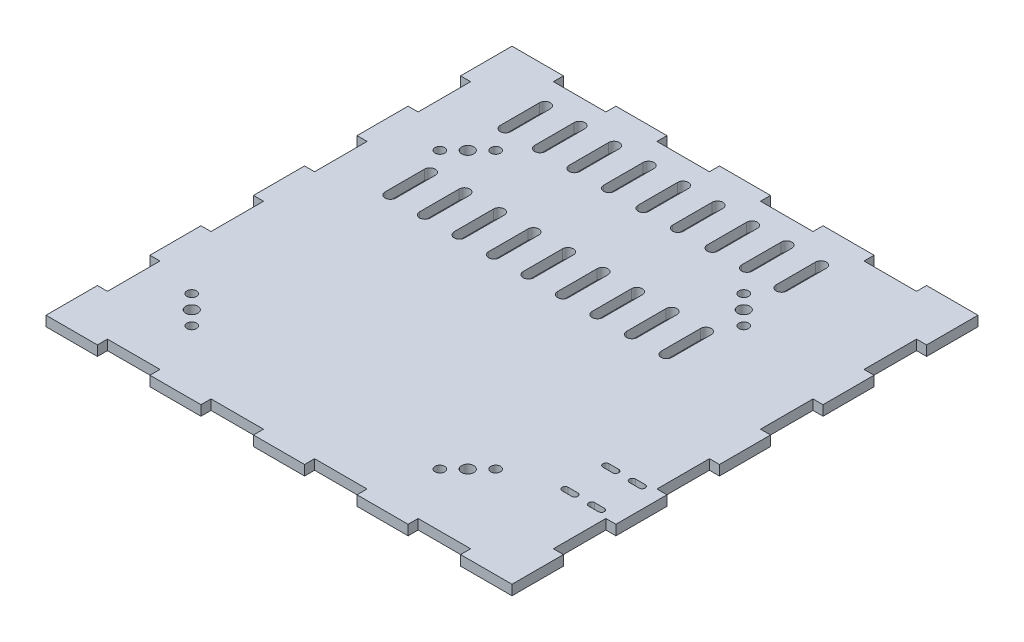
SolidWorks part; units mm, degrees
material "Acrylic (Medium-high impact)"
ref_plane "Front Plane" through (0, 0, 0) normal (0, 0, 1) x (1, 0, 0)
ref_plane "Top Plane" through (0, 0, 0) normal (0, 1, 0) x (1, 0, 0)
ref_plane "Right Plane" through (0, 0, 0) normal (1, 0, 0) x (0, 0, -1)
sketch "Board refrence" plane through (0, 0, 0) normal (0, 1, 0) x (1, 0, 0)
  line L0 (45, -19.76) -> (50, -19.76)
  line L1 (-42.5, -42.5) -> (42.5, -42.5)
  line L2 (-42.5, -42.5) -> (-42.5, 42.5)
  line L3 (-42.5, 42.5) -> (42.5, 42.5)
  line L4 (42.5, -42.5) -> (42.5, 42.5)
  line L5 (-42.5, -42.5) -> (42.5, 42.5) construction
  line L6 (-42.5, 42.5) -> (42.5, -42.5) construction
  line L7 (-50.8, 48.85) -> (50.8, 48.85)
  line L8 (-50.8, 48.85) -> (-50.8, 42.5)
  line L9 (-50.8, 42.5) -> (50.8, 42.5)
  line L10 (50.8, 48.85) -> (50.8, 42.5)
  line L11 (45, -27.76) -> (50, -27.76)
  line L12 (47.5, -27.76) -> (47.5, -19.76) construction
  circle A0 centre (-38.5, 38.5) radius 1.6
  circle A1 centre (-38.5, -38.5) radius 1.6
  circle A2 centre (38.5, -38.5) radius 1.6
  circle A3 centre (38.5, 38.5) radius 1.6
  point P0 (0, 0)
  point P14 (0, 42.5)
  point P15 (0, 42.5)
  point P26 (47.5, -23.76)
  dimension "D4" = 3.2
  dimension "D1" = 85
  dimension "D2" = 85
  dimension "D3" = 4
  dimension "D5" = 6.35
  dimension "D6" = 101.6
  dimension "D7" = 18.74
  dimension "D8" = 8
  dimension "D9" = 5
  dimension "D10" = 5
sketch "Sketch2" plane through (0, 0, 0) normal (0, 1, 0) x (1, 0, 0)
  line L0 (-42.5, -42.5) -> (-42.5, 42.5) construction
  line L1 (-54.3, 66.65) -> (69.3, 66.65) construction
  line L2 (-54.3, 66.65) -> (-54.3, -56.95) construction
  line L3 (-54.3, -56.95) -> (69.3, -56.95) construction
  line L4 (69.3, 66.65) -> (69.3, -56.95) construction
  line L6 (42.5, -42.5) -> (42.5, 42.5) construction
  line L7 (-50.8, 48.85) -> (50.8, 48.85) construction
  line L8 (-57.5, 69.85) -> (-57.5, -60.15)
  line L9 (-57.5, -60.15) -> (72.5, -60.15)
  line L10 (72.5, 69.85) -> (72.5, -60.15)
  line L11 (-57.5, 69.85) -> (72.5, 69.85)
  circle A0 centre (-38.5, 38.5) radius 1.7
  circle A1 centre (-38.5, -38.5) radius 1.7
  circle A2 centre (38.5, -38.5) radius 1.7
  circle A3 centre (38.5, 38.5) radius 1.7
  point P16 (0, 0)
  dimension "D1" = 3.4
  dimension "D2" = 15
  dimension "D3" = 21
  dimension "D4" = 30
  dimension "D6" = 130
  dimension "D5" = 3.2
extrude "Boss-Extrude1" add sketch "Sketch2" along normal blind 2.8
sketch "Sketch5" plane through (0, 2.8, 0) normal (0, 1, 0) x (1, 0, 0)
  line L0 (34.6109, 42.3891) -> (42.3891, 34.6109) construction
  line L1 (72.5, -60.15) -> (72.5, 69.85) construction
  circle A0 centre (42.3891, 34.6109) radius 1.35
  circle A1 centre (34.6109, 42.3891) radius 1.35
  circle A2 centre (34.6109, -42.3891) radius 1.35
  circle A3 centre (42.3891, -34.6109) radius 1.35
  circle A4 centre (-42.3891, -34.6109) radius 1.35
  circle A5 centre (-34.6109, -42.3891) radius 1.35
  circle A6 centre (-34.6109, 42.3891) radius 1.35
  circle A7 centre (-42.3891, 34.6109) radius 1.35
  point P4 (38.5, 38.5)
  point P23 (0, 0)
  dimension "D3" = 2.7
  dimension "D1" = 45
  dimension "D2" = 11
extrude "Cut-Extrude2" cut sketch "Sketch5" against normal up to next
sketch "Sketch4" plane through (0, 2.8, 0) normal (0, 1, 0) x (1, 0, 0)
  line L0 (72.5, 55.4056) -> (72.5, 40.9611)
  line L1 (72.5, -60.15) -> (72.5, 69.85) construction
  line L2 (72.5, 12.0722) -> (69.7, 12.0722)
  line L3 (69.7, 12.0722) -> (69.7, 26.5167)
  line L4 (69.7, 26.5167) -> (72.5, 26.5167)
  line L5 (72.5, 26.5167) -> (72.5, 12.0722)
  line L6 (72.5, -16.8167) -> (69.7, -16.8167)
  line L7 (69.7, -16.8167) -> (69.7, -2.3722)
  line L8 (69.7, -2.3722) -> (72.5, -2.3722)
  line L9 (72.5, -2.3722) -> (72.5, -16.8167)
  line L10 (72.5, 40.9611) -> (69.7, 40.9611)
  line L11 (69.7, 40.9611) -> (69.7, 55.4056)
  line L12 (69.7, 55.4056) -> (72.5, 55.4056)
  line L13 (72.5, -45.7056) -> (69.7, -45.7056)
  line L14 (69.7, -45.7056) -> (69.7, -31.2611)
  line L15 (69.7, -31.2611) -> (72.5, -31.2611)
  line L16 (72.5, -31.2611) -> (72.5, -45.7056)
  line L17 (72.5, 40.9611) -> (72.5, 12.0722) construction
  line L18 (69.7, -45.7056) -> (69.7, -60.15) construction
  line L19 (-57.5, -60.15) -> (72.5, -60.15) construction
  line L20 (69.7, -31.2611) -> (69.7, -16.8167) construction
  line L21 (72.5, 69.85) -> (-57.5, 69.85) construction
  line L42 (-57.5, 69.85) -> (72.5, -60.15) construction
  line L66 (-43.0556, -60.15) -> (-43.0556, -57.35)
  line L67 (-43.0556, -57.35) -> (-28.6111, -57.35)
  line L68 (-28.6111, -57.35) -> (-28.6111, -60.15)
  line L91 (69.7, -2.3722) -> (69.7, 12.0722) construction
  line L92 (69.7, 26.5167) -> (69.7, 40.9611) construction
  line L93 (69.7, 55.4056) -> (69.7, 69.85) construction
  line L94 (-28.6111, -60.15) -> (-43.0556, -60.15)
  line L95 (-14.1667, -60.15) -> (-14.1667, -57.35)
  line L96 (-14.1667, -57.35) -> (0.2778, -57.35)
  line L97 (0.2778, -57.35) -> (0.2778, -60.15)
  line L103 (0.2778, -60.15) -> (-14.1667, -60.15)
  line L108 (14.7222, -60.15) -> (14.7222, -57.35)
  line L113 (14.7222, -57.35) -> (29.1667, -57.35)
  line L118 (29.1667, -57.35) -> (29.1667, -60.15)
  line L119 (29.1667, -60.15) -> (14.7222, -60.15)
  line L120 (58.0556, -60.15) -> (43.6111, -60.15)
  line L121 (43.6111, -60.15) -> (43.6111, -57.35)
  line L125 (43.6111, -57.35) -> (58.0556, -57.35)
  line L126 (58.0556, -57.35) -> (58.0556, -60.15)
  line L127 (-57.5, 55.4056) -> (-54.7, 55.4056)
  line L128 (-54.7, 55.4056) -> (-54.7, 40.9611)
  line L129 (-54.7, 40.9611) -> (-57.5, 40.9611)
  line L130 (-57.5, 40.9611) -> (-57.5, 55.4056)
  line L131 (-57.5, 26.5167) -> (-54.7, 26.5167)
  line L132 (-54.7, 26.5167) -> (-54.7, 12.0722)
  line L133 (-54.7, 12.0722) -> (-57.5, 12.0722)
  line L134 (-57.5, 12.0722) -> (-57.5, 26.5167)
  line L135 (-57.5, -2.3722) -> (-54.7, -2.3722)
  line L136 (-54.7, -2.3722) -> (-54.7, -16.8167)
  line L137 (-54.7, -16.8167) -> (-57.5, -16.8167)
  line L138 (-57.5, -16.8167) -> (-57.5, -2.3722)
  line L139 (-57.5, -45.7056) -> (-57.5, -31.2611)
  line L140 (-57.5, -31.2611) -> (-54.7, -31.2611)
  line L141 (-54.7, -31.2611) -> (-54.7, -45.7056)
  line L142 (-54.7, -45.7056) -> (-57.5, -45.7056)
  line L143 (58.0556, 69.85) -> (58.0556, 67.05)
  line L144 (58.0556, 67.05) -> (43.6111, 67.05)
  line L145 (43.6111, 67.05) -> (43.6111, 69.85)
  line L146 (43.6111, 69.85) -> (58.0556, 69.85)
  line L147 (29.1667, 69.85) -> (29.1667, 67.05)
  line L148 (29.1667, 67.05) -> (14.7222, 67.05)
  line L149 (14.7222, 67.05) -> (14.7222, 69.85)
  line L150 (14.7222, 69.85) -> (29.1667, 69.85)
  line L151 (0.2778, 69.85) -> (0.2778, 67.05)
  line L152 (0.2778, 67.05) -> (-14.1667, 67.05)
  line L153 (-14.1667, 67.05) -> (-14.1667, 69.85)
  line L154 (-14.1667, 69.85) -> (0.2778, 69.85)
  line L155 (-43.0556, 69.85) -> (-28.6111, 69.85)
  line L156 (-28.6111, 69.85) -> (-28.6111, 67.05)
  line L157 (-28.6111, 67.05) -> (-43.0556, 67.05)
  line L158 (-43.0556, 67.05) -> (-43.0556, 69.85)
  point P27 (7.5, 4.85)
  point P81 (7.5, 4.85)
  dimension "D4" = 2.8
  dimension "D1" = 4
  dimension "D2" = 4
extrude "Cut-Extrude1" cut sketch "Sketch4" against normal through all
sketch "Pad reference" plane through (0, 2.8, 0) normal (0, 1, 0) x (1, 0, 0)
  line L151 (72.5, -60.15) -> (72.5, -45.7056) construction
  line L152 (72.5, 69.85) -> (58.0556, 69.85) construction
  line L153 (-50.5, -53.15) -> (-43.0556, -53.15)
  line L154 (-50.5, -45.7056) -> (-50.5, -53.15)
  line L155 (-50.5, -53.15) -> (-43.0556, -53.15) construction
  line L156 (-50.5, -45.7056) -> (-50.5, -53.15) construction
  circle A0 centre (-50.5, 62.85) radius 4
  circle A1 centre (65.5, 62.85) radius 4
  circle A2 centre (65.5, -53.15) radius 4
  circle A3 centre (-50.5, -53.15) radius 4
  dimension "D1" = 8
  dimension "D3" = 7
  dimension "D4" = 7
  dimension "D2" = 7
sketch "Sketch6" plane through (0, 2.8, 0) normal (0, 1, 0) x (1, 0, 0)
  line L0 (67, -29.7389) -> (64.3, -29.7389) construction
  line L1 (67, -30.5889) -> (64.3, -30.5889)
  line L2 (67, -28.8889) -> (64.3, -28.8889)
  line L3 (59.6, -29.7389) -> (56.9, -29.7389) construction
  line L4 (59.6, -30.5889) -> (56.9, -30.5889)
  line L5 (59.6, -28.8889) -> (56.9, -28.8889)
  line L6 (72.5, -24.0389) -> (-49927.5, -24.0389) construction
  line L7 (72.5, -31.2611) -> (72.5, -16.8167) construction
  line L8 (59.6, -18.3389) -> (56.9, -18.3389) construction
  line L9 (59.6, -17.4889) -> (56.9, -17.4889)
  line L10 (59.6, -19.1889) -> (56.9, -19.1889)
  line L11 (67, -18.3389) -> (64.3, -18.3389) construction
  line L12 (67, -17.4889) -> (64.3, -17.4889)
  line L13 (67, -19.1889) -> (64.3, -19.1889)
  arc A0 (67, -30.5889) -> (67, -28.8889) centre (67, -29.7389) ccw
  arc A1 (64.3, -28.8889) -> (64.3, -30.5889) centre (64.3, -29.7389) ccw
  arc A2 (59.6, -30.5889) -> (59.6, -28.8889) centre (59.6, -29.7389) ccw
  arc A3 (56.9, -28.8889) -> (56.9, -30.5889) centre (56.9, -29.7389) ccw
  arc A4 (59.6, -17.4889) -> (59.6, -19.1889) centre (59.6, -18.3389) cw
  arc A5 (56.9, -19.1889) -> (56.9, -17.4889) centre (56.9, -18.3389) cw
  arc A6 (67, -17.4889) -> (67, -19.1889) centre (67, -18.3389) cw
  arc A7 (64.3, -19.1889) -> (64.3, -17.4889) centre (64.3, -18.3389) cw
  point P2 (65.65, -29.7389)
  point P7 (58.25, -29.7389)
  point P18 (72.5, -24.0389)
  point P21 (58.25, -18.3389)
  point P28 (65.65, -18.3389)
  dimension "D3" = 3
  dimension "D1" = 4.4
  dimension "D2" = 1.7
  dimension "D4" = 4.85
  dimension "D5" = 5.5
extrude "Cut-Extrude3" cut sketch "Sketch6" against normal up to next
sketch "Sketch7" plane through (0, 2.8, 0) normal (0, 1, 0) x (1, 0, 0)
  line L0 (-38.5, 60.05) -> (-38.5, 49.05) construction
  line L1 (-37, 60.05) -> (-37, 49.05)
  line L2 (-40, 60.05) -> (-40, 49.05)
  line L3 (-43.0556, 67.05) -> (-28.6111, 67.05) construction
  line L5 (-30.375, 60.05) -> (-30.375, 49.05)
  line L6 (-27.375, 60.05) -> (-27.375, 49.05)
  line L7 (-28.875, 60.05) -> (-28.875, 49.05) construction
  line L8 (-20.75, 60.05) -> (-20.75, 49.05)
  line L9 (-17.75, 60.05) -> (-17.75, 49.05)
  line L10 (-19.25, 60.05) -> (-19.25, 49.05) construction
  line L11 (-11.125, 60.05) -> (-11.125, 49.05)
  line L12 (-8.125, 60.05) -> (-8.125, 49.05)
  line L13 (-9.625, 60.05) -> (-9.625, 49.05) construction
  line L14 (-1.5, 60.05) -> (-1.5, 49.05)
  line L15 (1.5, 60.05) -> (1.5, 49.05)
  line L16 (0, 60.05) -> (0, 49.05) construction
  line L17 (8.125, 60.05) -> (8.125, 49.05)
  line L18 (11.125, 60.05) -> (11.125, 49.05)
  line L19 (9.625, 60.05) -> (9.625, 49.05) construction
  line L20 (17.75, 60.05) -> (17.75, 49.05)
  line L21 (20.75, 60.05) -> (20.75, 49.05)
  line L22 (19.25, 60.05) -> (19.25, 49.05) construction
  line L23 (27.375, 60.05) -> (27.375, 49.05)
  line L24 (30.375, 60.05) -> (30.375, 49.05)
  line L25 (28.875, 60.05) -> (28.875, 49.05) construction
  line L26 (37, 60.05) -> (37, 49.05)
  line L27 (40, 60.05) -> (40, 49.05)
  line L28 (38.5, 60.05) -> (38.5, 49.05) construction
  line L31 (-40, 27.95) -> (-40, 16.95)
  line L32 (-38.5, 38.5) -> (-38.5, 49.05) construction
  line L33 (-38.5, 38.5) -> (-38.5, 27.95) construction
  line L35 (-37, 27.95) -> (-37, 16.95)
  line L36 (-38.5, 27.95) -> (-38.5, 16.95) construction
  line L37 (-30.375, 27.95) -> (-30.375, 16.95)
  line L38 (-27.375, 27.95) -> (-27.375, 16.95)
  line L39 (-28.875, 27.95) -> (-28.875, 16.95) construction
  line L40 (-20.75, 27.95) -> (-20.75, 16.95)
  line L41 (-17.75, 27.95) -> (-17.75, 16.95)
  line L42 (-19.25, 27.95) -> (-19.25, 16.95) construction
  line L43 (-11.125, 27.95) -> (-11.125, 16.95)
  line L44 (-8.125, 27.95) -> (-8.125, 16.95)
  line L45 (-9.625, 27.95) -> (-9.625, 16.95) construction
  line L46 (-1.5, 27.95) -> (-1.5, 16.95)
  line L47 (1.5, 27.95) -> (1.5, 16.95)
  line L48 (0, 27.95) -> (0, 16.95) construction
  line L49 (8.125, 27.95) -> (8.125, 16.95)
  line L50 (11.125, 27.95) -> (11.125, 16.95)
  line L51 (9.625, 27.95) -> (9.625, 16.95) construction
  line L52 (17.75, 27.95) -> (17.75, 16.95)
  line L53 (20.75, 27.95) -> (20.75, 16.95)
  line L54 (19.25, 27.95) -> (19.25, 16.95) construction
  line L55 (27.375, 27.95) -> (27.375, 16.95)
  line L56 (30.375, 27.95) -> (30.375, 16.95)
  line L57 (28.875, 27.95) -> (28.875, 16.95) construction
  line L58 (37, 27.95) -> (37, 16.95)
  line L59 (40, 27.95) -> (40, 16.95)
  line L60 (38.5, 27.95) -> (38.5, 16.95) construction
  line L61 (38.5, 27.95) -> (38.5, 38.5) construction
  line L62 (38.5, 38.5) -> (38.5, 49.05) construction
  arc A0 (-37, 60.05) -> (-40, 60.05) centre (-38.5, 60.05) ccw
  arc A1 (-40, 49.05) -> (-37, 49.05) centre (-38.5, 49.05) ccw
  arc A2 (-27.375, 60.05) -> (-30.375, 60.05) centre (-28.875, 60.05) ccw
  arc A3 (-30.375, 49.05) -> (-27.375, 49.05) centre (-28.875, 49.05) ccw
  arc A4 (-17.75, 60.05) -> (-20.75, 60.05) centre (-19.25, 60.05) ccw
  arc A5 (-20.75, 49.05) -> (-17.75, 49.05) centre (-19.25, 49.05) ccw
  arc A6 (-8.125, 60.05) -> (-11.125, 60.05) centre (-9.625, 60.05) ccw
  arc A7 (-11.125, 49.05) -> (-8.125, 49.05) centre (-9.625, 49.05) ccw
  arc A8 (1.5, 60.05) -> (-1.5, 60.05) centre (0, 60.05) ccw
  arc A9 (-1.5, 49.05) -> (1.5, 49.05) centre (0, 49.05) ccw
  arc A10 (11.125, 60.05) -> (8.125, 60.05) centre (9.625, 60.05) ccw
  arc A11 (8.125, 49.05) -> (11.125, 49.05) centre (9.625, 49.05) ccw
  arc A12 (20.75, 60.05) -> (17.75, 60.05) centre (19.25, 60.05) ccw
  arc A13 (17.75, 49.05) -> (20.75, 49.05) centre (19.25, 49.05) ccw
  arc A14 (30.375, 60.05) -> (27.375, 60.05) centre (28.875, 60.05) ccw
  arc A15 (27.375, 49.05) -> (30.375, 49.05) centre (28.875, 49.05) ccw
  arc A16 (40, 60.05) -> (37, 60.05) centre (38.5, 60.05) ccw
  arc A17 (37, 49.05) -> (40, 49.05) centre (38.5, 49.05) ccw
  arc A18 (-37, 27.95) -> (-40, 27.95) centre (-38.5, 27.95) ccw
  arc A19 (-40, 16.95) -> (-37, 16.95) centre (-38.5, 16.95) ccw
  arc A20 (-27.375, 27.95) -> (-30.375, 27.95) centre (-28.875, 27.95) ccw
  arc A21 (-30.375, 16.95) -> (-27.375, 16.95) centre (-28.875, 16.95) ccw
  arc A22 (-17.75, 27.95) -> (-20.75, 27.95) centre (-19.25, 27.95) ccw
  arc A23 (-20.75, 16.95) -> (-17.75, 16.95) centre (-19.25, 16.95) ccw
  arc A24 (-8.125, 27.95) -> (-11.125, 27.95) centre (-9.625, 27.95) ccw
  arc A25 (-11.125, 16.95) -> (-8.125, 16.95) centre (-9.625, 16.95) ccw
  arc A26 (1.5, 27.95) -> (-1.5, 27.95) centre (0, 27.95) ccw
  arc A27 (-1.5, 16.95) -> (1.5, 16.95) centre (0, 16.95) ccw
  arc A28 (11.125, 27.95) -> (8.125, 27.95) centre (9.625, 27.95) ccw
  arc A29 (8.125, 16.95) -> (11.125, 16.95) centre (9.625, 16.95) ccw
  arc A30 (20.75, 27.95) -> (17.75, 27.95) centre (19.25, 27.95) ccw
  arc A31 (17.75, 16.95) -> (20.75, 16.95) centre (19.25, 16.95) ccw
  arc A32 (30.375, 27.95) -> (27.375, 27.95) centre (28.875, 27.95) ccw
  arc A33 (27.375, 16.95) -> (30.375, 16.95) centre (28.875, 16.95) ccw
  arc A34 (40, 27.95) -> (37, 27.95) centre (38.5, 27.95) ccw
  arc A35 (37, 16.95) -> (40, 16.95) centre (38.5, 16.95) ccw
  point P2 (-38.5, 54.55)
  point P12 (-40, 54.55)
  point P16 (-28.875, 54.55)
  point P23 (-19.25, 54.55)
  point P30 (-9.625, 54.55)
  point P37 (0, 54.55)
  point P44 (9.625, 54.55)
  point P51 (19.25, 54.55)
  point P58 (28.875, 54.55)
  point P65 (38.5, 54.55)
  point P75 (-38.5, 22.45)
  point P86 (-28.875, 22.45)
  point P93 (-19.25, 22.45)
  point P100 (-9.625, 22.45)
  point P107 (0, 22.45)
  point P114 (9.625, 22.45)
  point P121 (19.25, 22.45)
  point P128 (28.875, 22.45)
  point P135 (38.5, 22.45)
  dimension "D1" = 7
  dimension "D2" = 11
  dimension "D4" = 3
  dimension "D5" = 9
  dimension "D6" = 2
extrude "Cut-Extrude4" cut sketch "Sketch7" against normal up to next
other "Tolerance" face at (43.6111, 1.4, -68.45) face at (14.7222, 1.4, -68.45) face at (-14.1667, 1.4, -68.45) face at (-43.0556, 1.4, -68.45) face at (29.1667, 1.4, -68.45) face at (58.0556, 1.4, -68.45) face at (0.2778, 1.4, -68.45) face at (-28.6111, 1.4, -68.45) face at (-56.1, 1.4, -40.9611) face at (-56.1, 1.4, -55.4056) face at (-56.1, 1.4, -12.0722) face at (-56.1, 1.4, -26.5167) face at (-56.1, 1.4, 2.3722) face at (-56.1, 1.4, 16.8167) face at (-56.1, 1.4, 45.7056) face at (-56.1, 1.4, 31.2611) face at (-28.6111, 1.4, 58.75) face at (-43.0556, 1.4, 58.75) face at (-14.1667, 1.4, 58.75) face at (0.2778, 1.4, 58.75) face at (14.7222, 1.4, 58.75) face at (29.1667, 1.4, 58.75) face at (58.0556, 1.4, 58.75) face at (43.6111, 1.4, 58.75) face at (71.1, 1.4, 31.2611) face at (71.1, 1.4, 45.7056) face at (71.1, 1.4, 16.8167) face at (71.1, 1.4, 2.3722) face at (71.1, 1.4, -12.0722) face at (71.1, 1.4, -26.5167) face at (71.1, 1.4, -55.4056) face at (71.1, 1.4, -40.9611) parameters "D1"=0.1
equation "\"D5@Board refrence\" =  ( 1 / 4 )  * 1in"
equation "\"D6@Board refrence\" = 4in"
equation "\"slot_depth\"= 2.8mm"
equation "\"slot_width_tolerance\"= 0.0mm"
equation "\"D4@Sketch4\"=\"slot_depth\""
